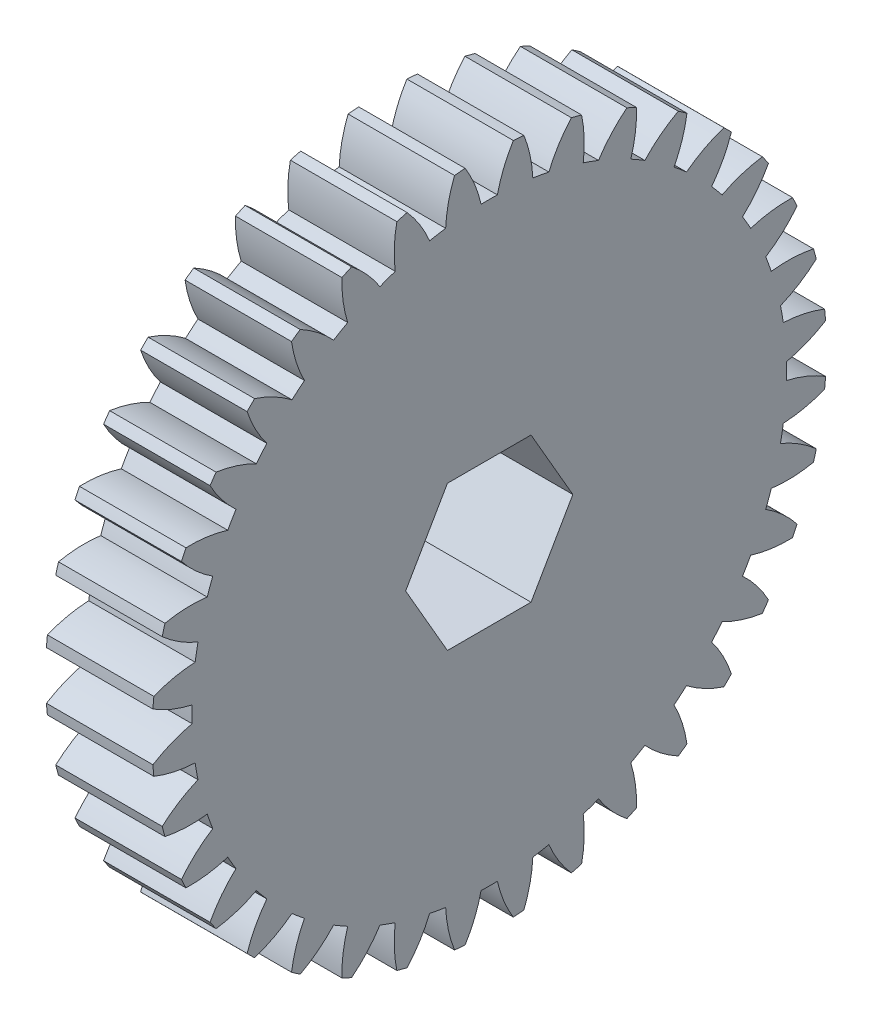
SolidWorks part; units mm, degrees
ref_plane "Plane1" through (0, 0, 0) normal (0, 0, 1) x (1, 0, 0)
ref_plane "Plane2" through (0, 0, 0) normal (0, 1, 0) x (1, 0, 0)
ref_plane "Plane3" through (0, 0, 0) normal (1, 0, 0) x (0, 0, -1)
other "Configuration Table"
sketch "HoldingSke" plane through (0, 0, 0) normal (0, 1, 0) x (1, 0, 0)
  line L0 (0, 0) -> (493.1768, -358.3139)
  line L1 (-15, 0) -> (100, 0) construction
  line L2 (0, 0) -> (-2.1039, 2.3779)
  line L3 (0, 0) -> (-11.863, 4.5341)
  line L4 (0, 0) -> (6.9867, 5.0761)
  line L5 (0, 0) -> (-47.5972, -17.7524)
  line L6 (0, 0) -> (-5.2639, -3.5516)
  line L7 (-2.1039, 2.3779) -> (8.8308, 51.9871)
  line L8 (-76.2, 54.61) -> (-75.184, 54.61)
  line L9 (-71.009, 38.7566) -> (-53.1078, 45.2721)
  line L10 (-76.2, 71.12) -> (104.1128, 71.12)
  line L11 (0, 0) -> (-6.35, 0)
  line L12 (-76.2, 101.6) -> (-76.1573, 101.6)
  line L13 (24.9733, 27.94) -> (52.9518, 28.4284)
  line L14 (24.9733, 27.94) -> (25.0241, 27.9398)
  line L15 (24.9733, 27.94) -> (100.4021, 29.52)
  circle A0 centre (0, 0) radius 0.3969
  circle A1 centre (0, 0) radius 17.7292
  circle A2 centre (0, 0) radius 38.1
  circle A3 centre (0, 0) radius 0.3969
  dimension "MHD" = 35.4584
  dimension "Hub_dia" = 76.2
  dimension "Bore" = 0.7937
  dimension "MBD" = 0.7937
  dimension "Num_teeth" = 36
  dimension "Pitch" = 609.6
  dimension "Overall_len" = 50.8
  dimension "Show_teeth" = 36
  dimension "Thickness" = 6.35
  dimension "OAL" = 50.8001
  dimension "T_dim" = 1.016
  dimension "Ap" = 20
  dimension "H" = 19.05
  dimension "Pitch_radius" = 180.3128
  dimension "Backlash" = 0.0427
  dimension "Addendum_fac" = 1
  dimension "Dedendum_fac" = 1.2
  dimension "Clearance_fac" = 0.2
  dimension "Dedendum_add" = 0.0508
sketch "BasProSke" plane through (0, 0, 0) normal (0, 1, 0) x (1, 0, 0)
  line L0 (-10, 0) -> (60, 0) construction
  line L1 (0, 0) -> (0, 20.1083)
  line L2 (0, 0) -> (6.35, 0)
  line L3 (6.35, 0) -> (6.35, 20.1083)
  line L4 (6.35, 20.1083) -> (0, 20.1083)
  dimension "Thickness" = 6.35
  dimension "Diameter" = 40.2167
revolve "Base-Revolve" add sketch "BasProSke" angle 360 about L0
sketch "TooCutSke" plane through (0, 0, 0) normal (1, 0, 0) x (0, 0, -1)
  line L1 (0, 0) -> (0, 107) construction
  line L2 (0, 0) -> (-0.9056, 19.0285) construction
  line L3 (0, 0) -> (-3.318, 37.9251) construction
  line L4 (-0.9056, 19.0285) -> (-1.659, 18.9625) construction
  arc A0 (0.4859, 17.7225) -> (-0.4859, 17.7225) centre (0, 0) ccw
  arc A1 (1.4524, 20.0813) -> (-1.4524, 20.0813) centre (0, 0) ccw
  circle A2 centre (0, 0) radius 19.05 construction
  circle A3 centre (0, 0) radius 17.9011 construction
  arc A4 (-0.4859, 17.7225) -> (-1.4524, 20.0813) centre (-7.9208, 16.0534) ccw
  arc A5 (1.4524, 20.0813) -> (0.4859, 17.7225) centre (7.9208, 16.0534) ccw
  dimension "Root_dia" = 35.4584
  dimension "Overcut_dia" = 40.2675
  dimension "Pitch_dia" = 38.1
  dimension "Base_dia" = 35.8023
  dimension "Flank_rad" = 7.62
  dimension "Half_ang" = 5
  dimension "Half_CT" = 0.7563
extrude "ToothCut" cut sketch "TooCutSke" along normal through all
fillet "Breaks" [suppressed] radius 0.0212
fillet "RootFillets" [suppressed] radius 0.2625
pattern_circular "TeethCuts" count 36 every 10 about axis through (-10, 0, 0) along (1, 0, 0) of "ToothCut", "RootFillets", "Breaks"
sketch "HubNeaOneSke" plane through (0, 0, 0) normal (-1, 0, 0) x (0, 0, 1)
  circle A0 centre (0, 0) radius 17.7292
  dimension "Diameter" = 35.4584
extrude "HubNearOne" [suppressed] add sketch "HubNeaOneSke" along normal blind 44.4501
sketch "HubNeaBotSke" plane through (0, 0, 0) normal (-1, 0, 0) x (0, 0, 1)
  circle A0 centre (0, 0) radius 17.7292
  dimension "Diameter" = 35.4584
extrude "HubNearBoth" [suppressed] add sketch "HubNeaBotSke" along normal blind 22.225
ref_plane "FarPln" through (6.35, 0, 0) normal (1, 0, 0) x (0, 0, -1)
sketch "HubFarSke" plane through (6.35, 0, 0) normal (1, 0, 0) x (0, 0, -1)
  circle A0 centre (0, 0) radius 17.7292
  dimension "Diameter" = 35.4584
extrude "HubFar" [suppressed] add sketch "HubFarSke" along normal blind 22.225
sketch "BorSke" plane through (0, 0, 0) normal (1, 0, 0) x (0, 0, -1)
  circle A0 centre (0, 0) radius 0.3969
  dimension "Diameter" = 0.7937
extrude "Bore" cut sketch "BorSke" along normal mid plane 101.6001
sketch "KeySke" plane through (0, 0, 0) normal (1, 0, 0) x (0, 0, -1)
  line L0 (-0.127, 0) -> (-0.127, 0.6191)
  line L1 (-0.127, 0.6191) -> (0.127, 0.6191)
  line L2 (0.127, 0.6191) -> (0.127, 0)
  line L3 (0, 0) -> (0, 34) construction
  line L4 (-0.127, 0) -> (0.127, 0)
  dimension "Offset" = 0.6191
extrude "Keyway" [suppressed] cut sketch "KeySke" along normal mid plane 101.6001
pattern_circular "Keyway2" [suppressed] count 2 every 90 about axis through (-10, 0, 0) along (1, 0, 0)
sketch "Sketch1" plane through (6.35, 0, 0) normal (1, 0, 0) x (0, 0, -1)
  line L0 (-2.493, 4.318) -> (2.493, 4.318)
  line L1 (2.493, 4.318) -> (4.986, 0)
  line L2 (4.986, 0) -> (2.493, -4.318)
  line L3 (2.493, -4.318) -> (-2.493, -4.318)
  line L4 (-2.493, -4.318) -> (-4.986, 0)
  line L5 (-4.986, 0) -> (-2.493, 4.318)
  line L6 (0, 4.318) -> (0, -4.318) construction
  line L7 (-4.986, 0) -> (4.986, 0) construction
  point P2 (0, 0)
  point P9 (3.1654, 0)
  point P11 (1.5481, 4.2128)
  point P12 (1.8008, -3.7477)
  point P14 (3.3567, 4.5431)
  point P15 (-5.0469, 0)
  dimension "D1" = 8.636
  dimension "D2" = 8.636
extrude "Cut-Extrude1" cut sketch "Sketch1" against normal through all
equation "' \"Pitch@HoldingSke\" = 4"
equation "' \"Num_teeth@HoldingSke\" = 12"
equation "' \"Ap@HoldingSke\" =  20"
equation "' \"Ap@HoldingSke\" = 20"
equation "' \"Width@HoldingSke\" = 0.5"
equation "' \"Hub_dia@HoldingSke\"= 1"
equation "' \"Hub_dia@HoldingSke\" = 1"
equation "' \"Overall_len@HoldingSke\" = 1.0"
equation "' \"Bore@HoldingSke\" = 0.75"
equation "' \"T_dim@HoldingSke\" = 0.85"
equation "' \"Width@KeySke\" = 0.25"
equation "' \"Show_teeth@HoldingSke\" = 13"
equation "' \"Backlash@HoldingSke\" = 0.009"
equation "' \"Addendum_fac@HoldingSke\" = 1.0"
equation "' \"Dedendum_fac@HoldingSke\" = 1.25"
equation "' \"Dedendum_add@HoldingSke\" = 0.00005"
equation "' \"Clearance_fac@HoldingSke\" = 0.25"
equation "' \"Pitch@HoldingSke\" = 0.5"
equation "' \"Num_teeth@HoldingSke\" = 23"
equation "' \"Show_teeth@HoldingSke\" = 23"
equation "' \"Backlash@HoldingSke\" = 0.0375"
equation "\"Overcut_dia@TooCutSke\" = (\"Num_teeth@HoldingSke\" + 2 * \"Addendum_fac@HoldingSke\") / \"Pitch@HoldingSke\" + 0.002"
equation "\"Pitch_dia@TooCutSke\" = \"Num_teeth@HoldingSke\" / \"Pitch@HoldingSke\""
equation "\"Base_dia@TooCutSke\" = \"Num_teeth@HoldingSke\" / \"Pitch@HoldingSke\" * cos((\"Ap@HoldingSke\"  * 3.14159265 / 180))"
equation "\"Root_dia@TooCutSke\" = (\"Num_teeth@HoldingSke\" + 2) / \"Pitch@HoldingSke\" - 2 * (\"Addendum_fac@HoldingSke\" + \"Dedendum_fac@HoldingSke\") / \"Pitch@HoldingSke\" - \"Dedendum_add@HoldingSke\" * 2"
equation "\"Half_ang@TooCutSke\" = 180 / \"Num_teeth@HoldingSke\""
equation "\"Half_CT@TooCutSke\" = \"Num_teeth@HoldingSke\" / \"Pitch@HoldingSke\" * sin((3.14159265 / 2 / \"Num_teeth@HoldingSke\")) / 2 - 7 * \"Backlash@HoldingSke\" / 4"
equation "\"Flank_rad@TooCutSke\" = \"Num_teeth@HoldingSke\" / \"Pitch@HoldingSke\" / 5"
equation "\"Radius@RootFillets\" = \"Clearance_fac@HoldingSke\" / \"Pitch@HoldingSke\" + \"Dedendum_add@HoldingSke\""
equation "\"Break_rad@Breaks\" = 0.02 / \"Pitch@HoldingSke\""
equation "\"Thickness@HoldingSke\" = \"Width@HoldingSke\""
equation "\"OAL@HoldingSke\" = \"Thickness@HoldingSke\""
equation "\"MHD@HoldingSke\" = (\"Num_teeth@HoldingSke\" + 2) / \"Pitch@HoldingSke\" - 2 * (\"Addendum_fac@HoldingSke\" + \"Dedendum_fac@HoldingSke\")  / \"Pitch@HoldingSke\" - \"Dedendum_add@HoldingSke\" * 2"
equation "\"MBD@HoldingSke\" = (\"Num_teeth@HoldingSke\" + 2) / \"Pitch@HoldingSke\" - 2 * (\"Addendum_fac@HoldingSke\" + \"Dedendum_fac@HoldingSke\")  / \"Pitch@HoldingSke\" - \"Dedendum_add@HoldingSke\" * 2 - 0.002"
equation "\"MHD@HoldingSke\" = ((sgn( \"MHD@HoldingSke\" - \"Hub_dia@HoldingSke\" )-1)*( \"MHD@HoldingSke\" - \"Hub_dia@HoldingSke\" ))/-2+ \"Hub_dia@HoldingSke\""
equation "\"MBD@HoldingSke\" = ((sgn( \"MBD@HoldingSke\" - \"Bore@HoldingSke\" )-1)*( \"MBD@HoldingSke\" - \"Bore@HoldingSke\" ))/-2+ \"Bore@HoldingSke\""
equation "\"OAL@HoldingSke\" = ((sgn( \"OAL@HoldingSke\" - \"Overall_len@HoldingSke\" )+1)*( \"OAL@HoldingSke\" - \"Overall_len@HoldingSke\" ))/2 + \"Overall_len@HoldingSke\" + 0.000002"
equation "\"Num_teeth@TeethCuts\" = int( \"Show_teeth@HoldingSke\" ) + 1"
equation "\"Num_teeth@TeethCuts\" = ((sgn( \"Num_teeth@TeethCuts\" - \"Num_teeth@HoldingSke\" )-1)*( \"Num_teeth@TeethCuts\" - \"Num_teeth@HoldingSke\" ))/-2+ \"Num_teeth@HoldingSke\""
equation "\"Num_teeth@TeethCuts\" = ((sgn( \"Num_teeth@TeethCuts\" - 2.0)+1)*( \"Num_teeth@TeethCuts\" - 2.0))/2 +2.0"
equation "\"Angle@TeethCuts\" = 360.0 / \"Num_teeth@HoldingSke\""
equation "\"Diameter@BasProSke\" = (\"Num_teeth@HoldingSke\" + 2 * \"Addendum_fac@HoldingSke\") / \"Pitch@HoldingSke\""
equation "\"Thickness@BasProSke\"  = \"Thickness@HoldingSke\""
equation "' \"Fillet_rad@BasProSke\" =  \"Thickness@HoldingSke\" * 0.05"
equation "' \"Fillet_rad@BasProSke\" = \"Thickness@HoldingSke\" * 0.05"
equation "\"MHD@HoldingSke\" = ((sgn( \"MHD@HoldingSke\" - \"Root_dia@TooCutSke\" )-1)*( \"MHD@HoldingSke\" - \"Root_dia@TooCutSke\" ))/-2+ \"Root_dia@TooCutSke\""
equation "\"Diameter@HubNeaOneSke\" = \"MHD@HoldingSke\""
equation "\"Length@HubNearOne\" = \"OAL@HoldingSke\" - \"Thickness@BasProSke\""
equation "\"Diameter@HubNeaBotSke\" = \"MHD@HoldingSke\""
equation "\"Length@HubNearBoth\" = ( \"OAL@HoldingSke\" - \"Thickness@BasProSke\" ) / 2.0"
equation "\"Thickness@FarPln\" = \"Thickness@BasProSke\""
equation "\"Diameter@HubFarSke\" = \"MHD@HoldingSke\""
equation "\"Length@HubFar\" = ( \"OAL@HoldingSke\" - \"Thickness@BasProSke\" ) / 2.0"
equation "\"Diameter@BorSke\" = \"MBD@HoldingSke\""
equation "\"D1@Bore\" = \"OAL@HoldingSke\" * 2.0"
equation "\"D1@Keyway\" = \"OAL@HoldingSke\" * 2.0"
equation "\"Offset@KeySke\" = \"T_dim@HoldingSke\" - \"MBD@HoldingSke\" / 2.0"
